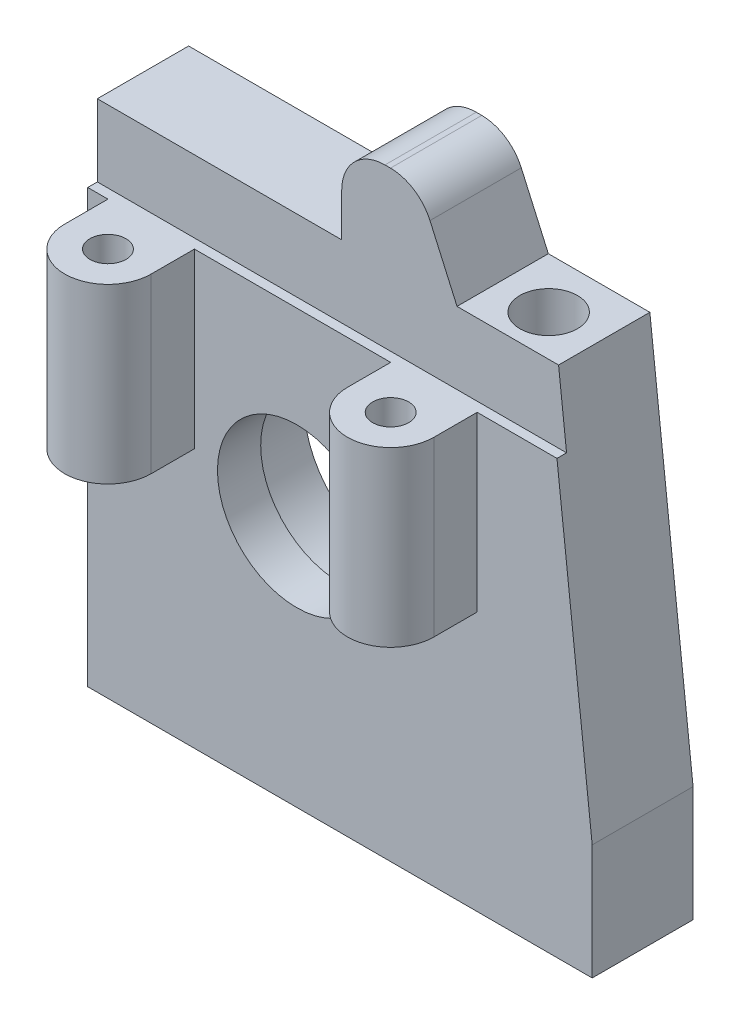
SolidWorks part; units mm, degrees
material "PBT General Purpose"
ref_plane "Front Plane" through (0, 0, 0) normal (0, 0, 1) x (1, 0, 0)
ref_plane "Top Plane" through (0, 0, 0) normal (0, 1, 0) x (1, 0, 0)
ref_plane "Right Plane" through (0, 0, 0) normal (1, 0, 0) x (0, 0, -1)
sketch "Sketch1" plane through (0, 0, 0) normal (0, 0, 1) x (1, 0, 0)
  line L0 (0, 0) -> (0, 35)
  line L1 (0, 35) -> (32, 35)
  line L2 (32, 35) -> (35, 8)
  line L3 (35, 8) -> (35, 0)
  line L4 (35, 0) -> (0, 0)
  circle A0 centre (14.5, 17.5) radius 5.5
  dimension "D7" = 11
  dimension "D1" = 35
  dimension "D2" = 32
  dimension "D3" = 35
  dimension "D4" = 8
  dimension "D5" = 17.5
  dimension "D6" = 14.5
extrude "Boss-Extrude1" add sketch "Sketch1" along normal blind 7
sketch "Sketch2" plane through (0, 0, 0) normal (0, -1, 0) x (1, 0, 0)
  line L0 (0, 7) -> (0, 0) construction
  circle A0 centre (6, 3.5) radius 1.25
  dimension "D2" = 2.5
  dimension "D1" = 6
extrude "Cut-Extrude1" cut sketch "Sketch2" against normal blind 12
cosmetic thread "Cosmetic Thread3" parameters "D2"=3
sketch "Sketch3" plane through (0, 0, 0) normal (0, -1, 0) x (1, 0, 0)
  line L0 (35, 7) -> (35, 0) construction
  circle A0 centre (24, 3.5) radius 1.25
  dimension "D2" = 2.5
  dimension "D1" = 11
extrude "Cut-Extrude2" cut sketch "Sketch3" against normal blind 12
cosmetic thread "Cosmetic Thread4" parameters "D2"=3
sketch "Sketch4" plane through (0, 0, 7) normal (0, 0, 1) x (1, 0, 0)
  line L0 (16.9569, 35) -> (16.9569, 41)
  line L1 (32, 35) -> (0, 35) construction
  line L2 (16.9569, 41) -> (22.2876, 41)
  line L3 (22.2876, 41) -> (24.9569, 35)
  line L4 (35, 8) -> (32, 35) construction
  line L5 (32, 35) -> (24.9569, 35)
  line L6 (16.9569, 35) -> (24.9569, 35)
  line L10 (0, 0) -> (35, 0)
  line L11 (35, 0) -> (35, 8)
  line L12 (35, 8) -> (32, 35)
  line L13 (32, 35) -> (0, 35)
  line L14 (0, 35) -> (0, 0)
  line L15 (0, 0) -> (35, 0)
  line L16 (35, 0) -> (35, 8)
  line L17 (35, 8) -> (32, 35)
  line L18 (16.9569, 35) -> (0, 35)
  line L19 (0, 35) -> (0, 0)
  line M10 (32, 35) -> (0, 35)
  dimension "D1" = 7
  dimension "D2" = 8
  dimension "D3" = 6
  dimension "D4" = 0
extrude "Boss-Extrude3" add sketch "Sketch4" against normal blind 7 contours L3 L2 L0 M10
fillet "Fillet1" radius 3 2 edges at (22.2876, 41, 3.5) (16.9569, 41, 3.5)
sketch "Sketch5" plane through (0, 0, 7) normal (0, 0, 1) x (1, 0, 0)
  circle A0 centre (19.9569, 38) radius 1
  dimension "D1" = 2
extrude "Cut-Extrude3" cut sketch "Sketch5" against normal blind 7
cosmetic thread "Cosmetic Thread8" parameters "D2"=3
ref_plane "Plane1" through (0, 18, 0) normal (0, 1, 0) x (1, 0, 0)
sketch "Sketch6" plane through (0, 18, 0) normal (0, 1, 0) x (1, 0, 0)
  line L0 (4.4016, -3.5267) -> (4.4016, -7) construction
  line L1 (16.9569, -7) -> (0, -7) construction
  line L2 (24.0183, 0) -> (24.0183, -7) construction
  line L3 (23.0798, 0) -> (24.9569, 0) construction
  line L4 (23.0798, -7) -> (24.9569, -7) construction
  line L6 (1.4016, -4) -> (7.4016, -4)
  line L7 (1.4016, -4) -> (1.4016, -10)
  line L8 (1.4016, -10) -> (7.4016, -10)
  line L9 (7.4016, -4) -> (7.4016, -10)
  line L10 (1.4016, -4) -> (7.4016, -10) construction
  line L11 (1.4016, -10) -> (7.4016, -4) construction
  line L12 (21.0183, -4) -> (27.0183, -4)
  line L13 (21.0183, -4) -> (21.0183, -10)
  line L14 (21.0183, -10) -> (27.0183, -10)
  line L15 (27.0183, -4) -> (27.0183, -10)
  line L16 (21.0183, -4) -> (27.0183, -10) construction
  line L17 (21.0183, -10) -> (27.0183, -4) construction
  circle A0 centre (4.4016, -10) radius 3
  circle A1 centre (24.0183, -10) radius 3
  point P14 (7.4016, -7)
  point P19 (27.0183, -7)
  dimension "D5" = 6
  dimension "D6" = 6
  dimension "D1" = 3
  dimension "D2" = 6
  dimension "D3" = 3
  dimension "D4" = 6
extrude "Boss-Extrude5" add sketch "Sketch6" along normal blind 12 contours L8 A0 | L13 L14 L15 L12 | A1
sketch "Sketch8" plane through (0, 30, 0) normal (0, 1, 0) x (1, 0, 0)
  circle A0 centre (4.4016, -10) radius 1.25
  circle A1 centre (24.0183, -10) radius 1.25
  dimension "D1" = 2.5
  dimension "D2" = 2.5
extrude "Cut-Extrude4" cut sketch "Sketch8" against normal blind 10
cosmetic thread "Cosmetic Thread5" parameters "D2"=3
cosmetic thread "Cosmetic Thread6" parameters "D2"=3
sketch "Sketch9" plane through (0, 35, 0) normal (0, 1, 0) x (1, 0, 0)
  circle A0 centre (28.4785, -3.5) radius 2
  dimension "D1" = 4
extrude "Cut-Extrude5" cut sketch "Sketch9" against normal blind 24
sketch "Sketch10" plane through (0, 0, 0) normal (0, 0, -1) x (-1, 0, 0)
  line L0 (-32, 35) -> (-24.9569, 35) construction
  line L1 (-31.1094, 21) -> (-26.1094, 21)
  line L2 (-31.1094, 21) -> (-31.1094, 15)
  line L3 (-31.1094, 15) -> (-26.1094, 15)
  line L4 (-26.1094, 21) -> (-26.1094, 15)
  line L5 (-31.1094, 21) -> (-26.1094, 15) construction
  line L6 (-31.1094, 15) -> (-26.1094, 21) construction
  point P0 (-28.6094, 18)
  dimension "D1" = 14
  dimension "D2" = 6
  dimension "D3" = 5
extrude "Cut-Extrude6" cut sketch "Sketch10" against normal blind 4
sketch "Sketch11" plane through (0, 0, 0) normal (0, 0, -1) x (-1, 0, 0)
  circle A0 centre (-29.943, 5.4996) radius 1.25
  dimension "D1" = 2.5
sketch "Sketch12" plane through (0, 0, 0) normal (0, 0, -1) x (-1, 0, 0)
  circle A0 centre (-14.5, 17.5) radius 6.5
  dimension "D1" = 13
extrude "Cut-Extrude9" cut sketch "Sketch12" against normal blind 4
ref_plane "Plane2" through (0, 41, 0) normal (0, 1, 0) x (1, 0, 0)
sketch "Sketch13" plane through (0, 41, 0) normal (0, 1, 0) x (1, 0, 0)
  line L0 (35, -7) -> (35, 0) construction
  line L1 (0, -7) -> (35, -7)
  line L2 (0, -7) -> (0, -6.7419)
  line L3 (0, -6.7419) -> (35, -6.7419)
  line L4 (35, -7) -> (35, -6.7419)
extrude "Cut-Extrude10" cut sketch "Sketch13" against normal blind 11
sketch "Sketch14" plane through (0, 41, 0) normal (0, 1, 0) x (1, 0, 0)
  line L1 (0, -6.7419) -> (33.4369, -6.7419)
  line L2 (0, -6.7419) -> (0, -6.3348)
  line L3 (0, -6.3348) -> (33.4369, -6.3348)
  line L4 (33.4369, -6.7419) -> (33.4369, -6.3348)
extrude "Cut-Extrude11" cut sketch "Sketch14" against normal blind 11
sketch "Sketch15" plane through (0, 0, 6.3348) normal (0, 0, 1) x (1, 0, 0)
  circle A0 centre (19.9569, 38) radius 1
extrude "Boss-Extrude6" add sketch "Sketch15" against normal blind 2
sketch "Sketch16" plane through (0, 0, 0) normal (0, 0, -1) x (-1, 0, 0)
  circle A0 centre (-29.943, 5.4996) radius 1.25
  dimension "D1" = 2.5
extrude "Cut-Extrude12" cut sketch "Sketch16" against normal blind 5
cosmetic thread "Cosmetic Thread9" parameters "D2"=3
